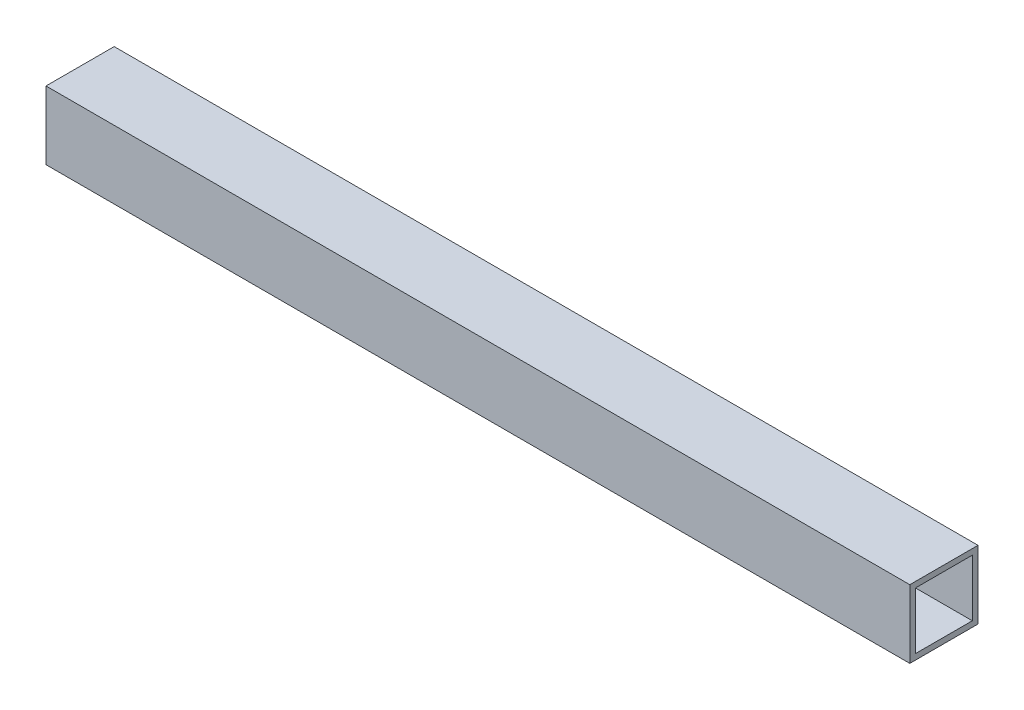
SolidWorks part; units mm, degrees
ref_plane "Front Plane" through (0, 0, 0) normal (0, 0, 1) x (1, 0, 0)
ref_plane "Top Plane" through (0, 0, 0) normal (0, 1, 0) x (1, 0, 0)
ref_plane "Right Plane" through (0, 0, 0) normal (1, 0, 0) x (0, 0, -1)
sketch "Sketch1" plane through (0, 0, 0) normal (1, 0, 0) x (0, 0, -1)
  line L1 (-7.9375, -7.9375) -> (7.9375, -7.9375)
  line L2 (-7.9375, -7.9375) -> (-7.9375, 7.9375)
  line L3 (-7.9375, 7.9375) -> (7.9375, 7.9375)
  line L4 (7.9375, -7.9375) -> (7.9375, 7.9375)
  line L5 (-7.9375, -7.9375) -> (7.9375, 7.9375) construction
  line L6 (-7.9375, 7.9375) -> (7.9375, -7.9375) construction
  line L7 (-9.525, -9.525) -> (9.525, -9.525)
  line L8 (-9.525, -9.525) -> (-9.525, 9.525)
  line L9 (-9.525, 9.525) -> (9.525, 9.525)
  line L10 (9.525, -9.525) -> (9.525, 9.525)
  line L11 (-9.525, -9.525) -> (9.525, 9.525) construction
  line L12 (-9.525, 9.525) -> (9.525, -9.525) construction
  point P0 (0, 0)
  point P6 (0, 0)
  dimension "D1" = 19.05
  dimension "D2" = 1.5875
extrude "Boss-Extrude1" add sketch "Sketch1" along normal blind 241.3
sketch "Sketch2" plane through (0, -9.525, 0) normal (0, -1, 0) x (1, 0, 0)
  line L0 (241.3, 0) -> (0, 0) construction
  line L1 (241.3, 9.525) -> (241.3, -9.525) construction
  line L2 (0, 9.525) -> (0, -9.525) construction
  point P6 (120.65, 0)
